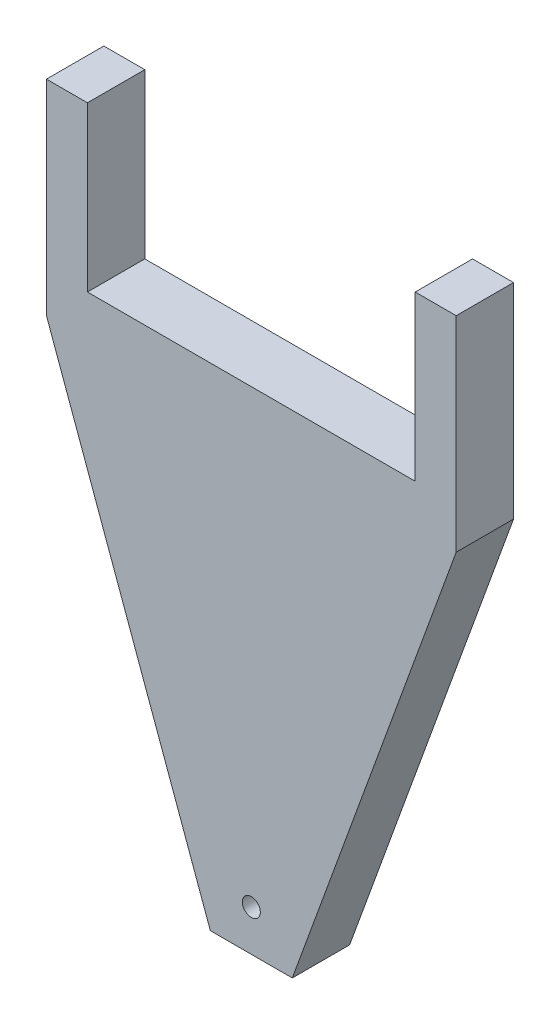
SolidWorks part; units mm, degrees
ref_plane "Alzado" through (0, 0, 0) normal (0, 0, 1) x (1, 0, 0)
ref_plane "Planta" through (0, 0, 0) normal (0, 1, 0) x (1, 0, 0)
ref_plane "Vista lateral" through (0, 0, 0) normal (1, 0, 0) x (0, 0, -1)
sketch "Croquis1" plane through (0, 0, 0) normal (0, 0, 1) x (1, 0, 0)
  line L0 (-20, 10) -> (-25, 10)
  line L1 (-20, 10) -> (20, 10)
  line L2 (-20, 10) -> (-20, -10)
  line L3 (-20, -10) -> (20, -10)
  line L4 (20, 10) -> (20, -10)
  line L5 (-20, 10) -> (20, -10) construction
  line L6 (-20, -10) -> (20, 10) construction
  line L7 (25, -15) -> (-25, -15)
  line L8 (25, -15) -> (25, 15)
  line L9 (25, 15) -> (-25, 15)
  line L10 (-25, -15) -> (-25, 15)
  line L11 (25, -15) -> (-25, 15) construction
  line L12 (25, 15) -> (-25, -15) construction
  line L13 (20, 10) -> (25, 10)
  point P0 (0, 0)
  point P5 (0, 0)
  dimension "D1" = 40
  dimension "D2" = 20
  dimension "D3" = 5
  dimension "D4" = 5
extrude "Saliente-Extruir1" add sketch "Croquis1" along normal blind 7 contours L13 L4 L3 L2 L0 L10 L7 L8
sketch "Croquis2" plane through (0, 0, 7) normal (0, 0, 1) x (1, 0, 0)
  line L0 (0, -15) -> (0, -65) construction
  line L1 (25, -15) -> (-25, -15) construction
  line L2 (25, -15) -> (5, -70)
  line L3 (5, -70) -> (-5, -70)
  line L4 (5, -70) -> (5, -60)
  line L5 (5, -60) -> (-5, -60)
  line L6 (-5, -70) -> (-5, -60)
  line L7 (5, -70) -> (-5, -60) construction
  line L8 (5, -60) -> (-5, -70) construction
  line L9 (-5, -70) -> (-25, -15)
  circle A0 centre (0, -65) radius 1.1
  line M8 (-25, -15) -> (25, -15)
  dimension "D1" = 2.2
  dimension "D2" = 10
  dimension "D3" = 50
extrude "Saliente-Extruir2" add sketch "Croquis2" against normal blind 7 contours L9 L6 L5 L4 L2 M8 | L6 L3 L4 L5 A0
